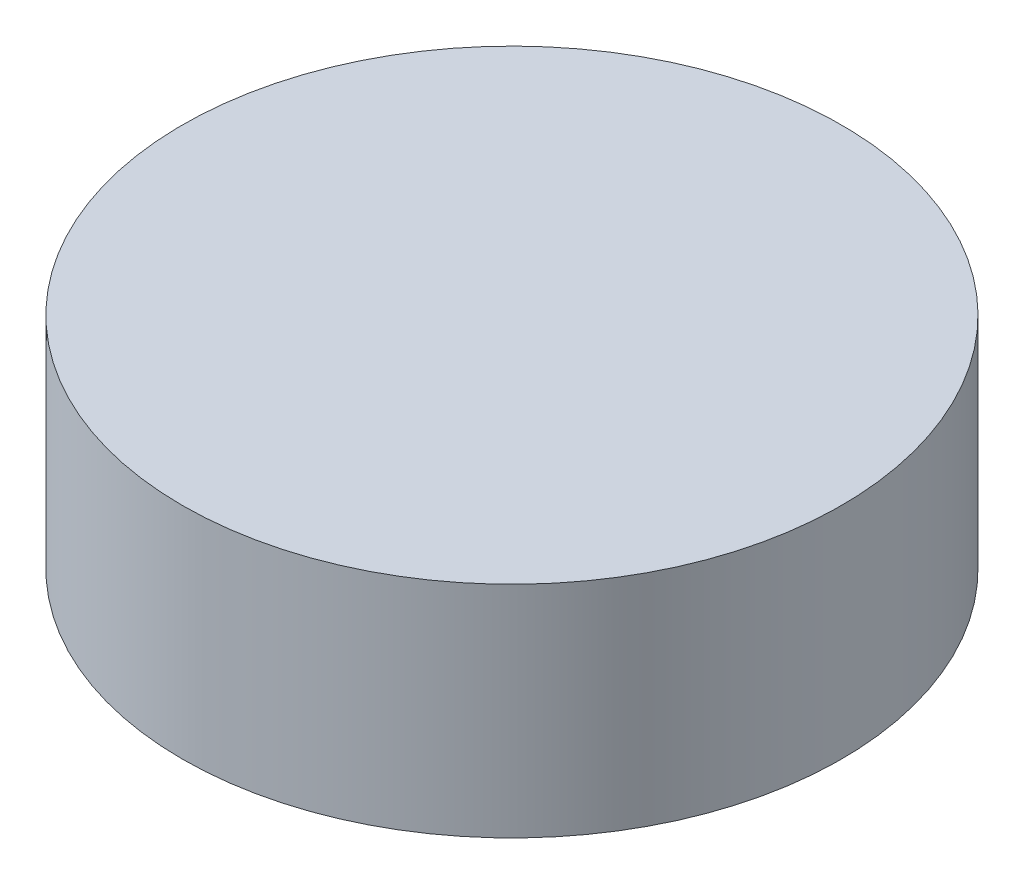
SolidWorks part; units mm, degrees
material "Zinc AC41A Alloy, As Cast"
ref_plane "Front Plane" through (0, 0, 0) normal (0, 0, 1) x (1, 0, 0)
ref_plane "Top Plane" through (0, 0, 0) normal (0, 1, 0) x (1, 0, 0)
ref_plane "Right Plane" through (0, 0, 0) normal (1, 0, 0) x (0, 0, -1)
sketch "Sketch1" plane through (0, 0, 0) normal (0, 1, 0) x (1, 0, 0)
  circle A0 centre (0, 0) radius 4.7625
  dimension "D1" = 9.525
extrude "Boss-Extrude1" add sketch "Sketch1" along normal blind 3.175
